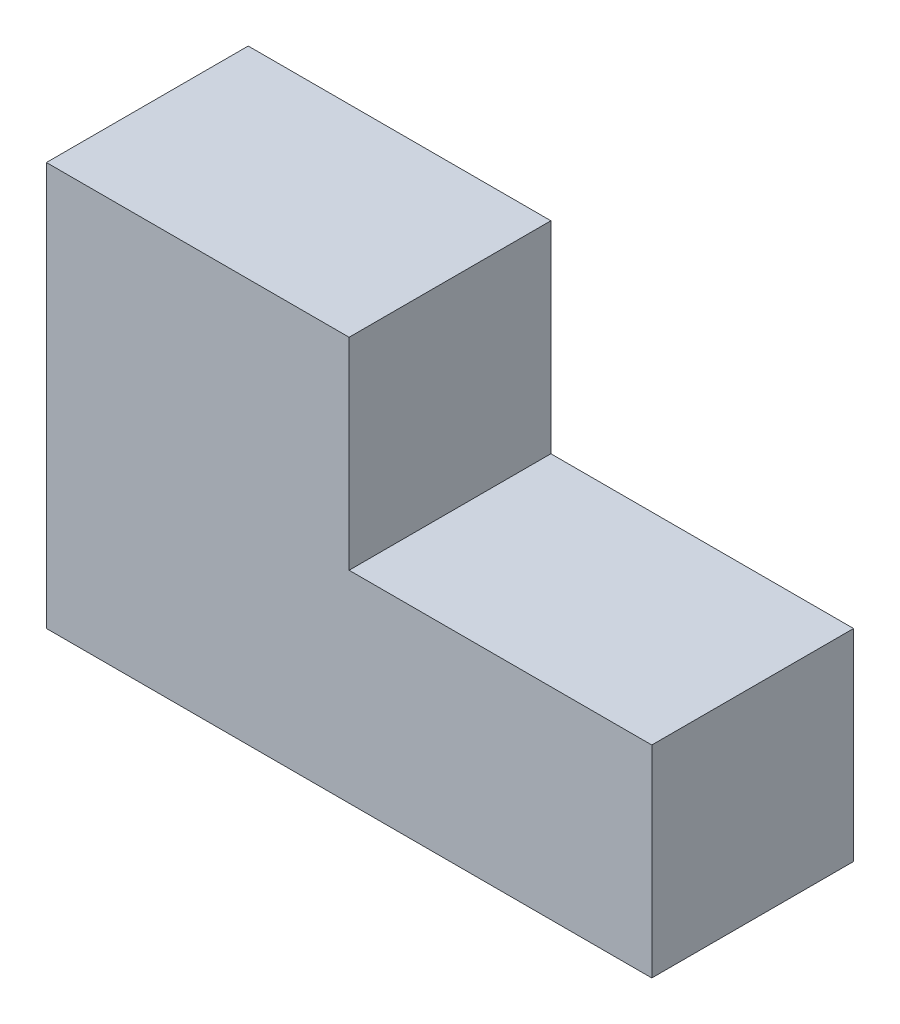
SolidWorks part; units mm, degrees
ref_plane "前视基准面" through (0, 0, 0) normal (0, 0, 1) x (1, 0, 0)
ref_plane "上视基准面" through (0, 0, 0) normal (0, 1, 0) x (1, 0, 0)
ref_plane "右视基准面" through (0, 0, 0) normal (1, 0, 0) x (0, 0, -1)
sketch "草图1" plane through (0, 0, 0) normal (0, 0, 1) x (1, 0, 0)
  line L0 (0, 0) -> (60, 0)
  line L1 (60, 0) -> (60, 20)
  line L2 (60, 20) -> (30, 20)
  line L3 (30, 20) -> (30, 40)
  line L4 (30, 40) -> (0, 40)
  line L5 (0, 40) -> (0, 0)
extrude "凸台-拉伸1" add sketch "草图1" along normal blind 20
